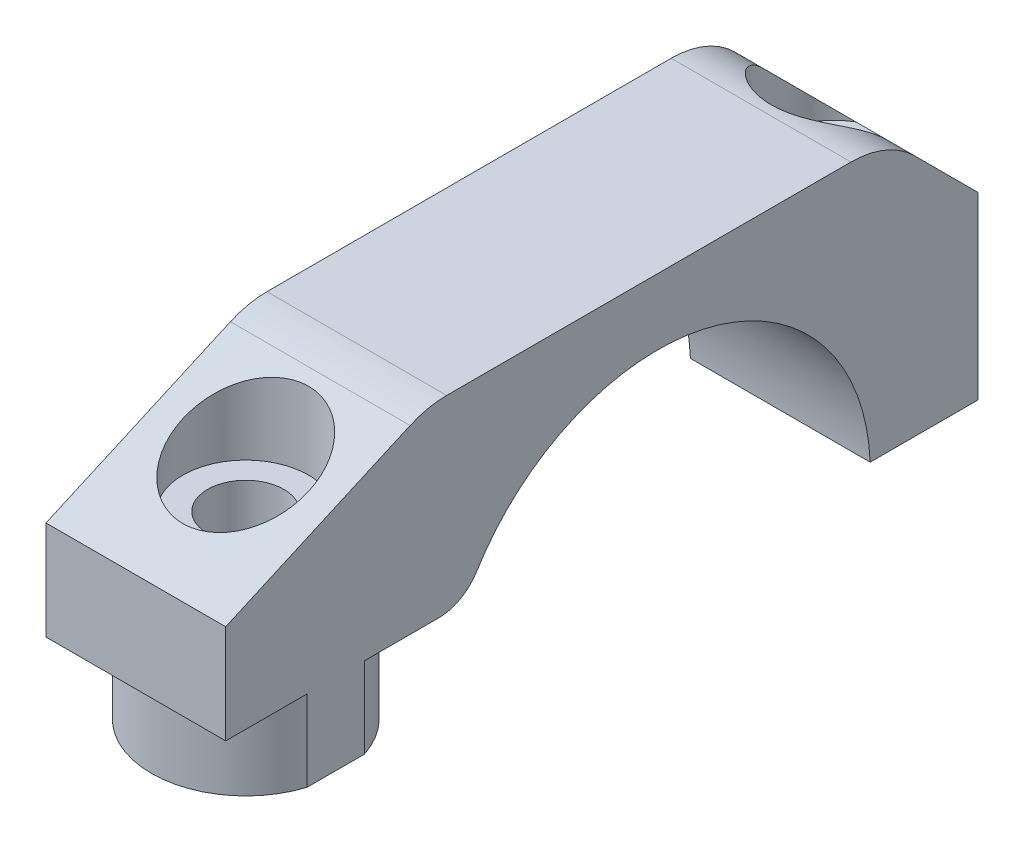
SolidWorks part; units mm, degrees
material "2014 Alloy"
ref_plane "Front Plane" through (0, 0, 0) normal (0, 0, 1) x (1, 0, 0)
ref_plane "Top Plane" through (0, 0, 0) normal (0, 1, 0) x (1, 0, 0)
ref_plane "Right Plane" through (0, 0, 0) normal (1, 0, 0) x (0, 0, -1)
sketch "Sketch1" plane through (0, 0, 0) normal (1, 0, 0) x (0, 0, -1)
  line L0 (-35.6288, 0) -> (35.6288, 0)
  line L1 (35.6288, 0) -> (35.6288, -30)
  line L2 (35.6288, -30) -> (23.6288, -30)
  line L3 (0, 0) -> (0, -31) construction
  line L4 (-24.6288, -30) -> (-48.0833, -30)
  line L5 (-35.6288, 0) -> (-35.6288, -30) construction
  line L6 (-24.6288, -30) -> (-24.6288, -21)
  line L7 (-48.0833, -30) -> (-48.0833, 0)
  line L8 (-48.0833, 0) -> (-35.6288, 0)
  line L9 (-24.6288, -21) -> (-21.4318, -21)
  arc A0 (23.6288, -30) -> (-21.4318, -21) centre (0, -31) ccw
  point P6 (-23.6288, -30)
  point P9 (-35.8561, -30)
  dimension "D1" = 23.65
  dimension "D2" = 12
  dimension "D3" = 30
  dimension "D4" = 35.87
  dimension "D5" = 1
  dimension "D6" = 9
  dimension "D7" = 11
  dimension "D8" = 83.7121
extrude "Boss-Extrude1" add sketch "Sketch1" along normal blind 20
chamfer "Chamfer1" distance 10 angle 45 1 edges at (10, 0, -35.6288)
chamfer "Chamfer2" distance 10 angle 66 1 edges at (10, 0, 48.0833)
fillet "Fillet2" radius 10 2 edges at (10, 0, -25.6288) (10, 0, 25.6229)
fillet "Fillet3" radius 5 1 edges at (10, -21, 21.4318)
hole_wizard "Ø8.5 (8.5) Diameter Hole1" positions "Sketch5" profile "Sketch4" hole size "Ø8.5" standard "ISO" end condition through all
sketch "Sketch5" plane through (0, -30, 0) normal (0, -1, 0) x (-1, 0, 0)
  line L0 (-10, -48.0833) -> (-10, -23.6288) construction
  line L4 (-10, 23.6288) -> (-10, 35.6288) construction
  line L5 (-20, 23.6288) -> (0, 23.6288) construction
  line L6 (-20, 35.6288) -> (0, 35.6288) construction
  line L8 (-20, -48.0833) -> (0, -48.0833) construction
  point P0 (-10, -35.8561)
  point P2 (-10, 29.6288)
sketch "Sketch4" plane through (10, -30, 35.8561) normal (1, 0, 0) x (0, 0, -1)
  line L0 (0, 0) -> (0, 30)
  line L1 (0, 30) -> (4.25, 30)
  line L2 (4.25, 30) -> (4.25, 0)
  line L5 (4.25, 0) -> (0, 0)
  line L11 (0, -6.35) -> (0, 107.95) construction
  dimension "Thru Hole Dia." = 8.5
  dimension "Thru Hole Depth" = 30
sketch "Sketch6" plane through (0, 0, 0) normal (0, 1, 0) x (1, 0, 0)
  circle A0 centre (10, -35.8561) radius 7
  circle A1 centre (10, 29.6288) radius 7
  circle A4 centre (10, -35.8561) radius 4.25 construction
  arc A5 (5.8872, 28.5578) -> (14.1128, 28.5578) centre (10, 29.6288) ccw construction
  dimension "D1" = 14
extrude "Cut-Extrude1" cut sketch "Sketch6" against normal blind 10
sketch "Sketch7" plane through (0, -30, 0) normal (0, -1, 0) x (1, 0, 0)
  circle A0 centre (10, 35.8561) radius 10.5
  circle A1 centre (10, 35.8561) radius 22.104
  dimension "D1" = 21
extrude "Cut-Extrude2" cut sketch "Sketch7" against normal offset from surface (9 mm away) 21 up to face at (10, 0, 1.0053)
sketch "Sketch8" [suppressed] plane through (20, 0, 0) normal (1, 0, 0) x (0, 0, -1)
  line L9 (-24.5288, -21) -> (-24.292, -21)
  line L10 (23.5288, -30) -> (35.5288, -30)
  line L11 (35.5288, -30) -> (35.5288, -10)
  line L12 (35.5288, -10) -> (28.4577, -2.9289)
  line L13 (21.3866, 0) -> (-23.5974, 0)
  line L14 (-27.6648, -0.8645) -> (-48.1834, -10)
  line L15 (-48.1834, -10) -> (-48.1834, -30)
  line L16 (-48.1834, -30) -> (-24.5288, -30)
  line L17 (-24.5288, -30) -> (-24.5288, -21)
  line L18 (-24.5288, -21) -> (-24.292, -21)
  line L19 (23.5288, -30) -> (35.5288, -30)
  line L20 (35.5288, -30) -> (35.5288, -10)
  line L21 (35.5288, -10) -> (28.4577, -2.9289)
  line L22 (21.3866, 0) -> (-23.5974, 0)
  line L23 (-27.6648, -0.8645) -> (-48.1834, -10)
  line L24 (-48.1834, -10) -> (-48.1834, -30)
  line L25 (-48.1834, -30) -> (-24.5288, -30)
  line L26 (-24.5288, -30) -> (-24.5288, -21)
  arc A4 (-24.292, -21) -> (-20.0377, -18.627) centre (-24.292, -16) ccw
  arc A5 (23.5288, -30) -> (-20.0377, -18.627) centre (0, -31) ccw
  arc A6 (28.4577, -2.9289) -> (21.3866, 0) centre (21.3866, -10) ccw
  arc A7 (-23.5974, 0) -> (-27.6648, -0.8645) centre (-23.5974, -10) ccw
  arc A8 (-24.292, -21) -> (-20.0377, -18.627) centre (-24.292, -16) ccw
  arc A9 (23.5288, -30) -> (-20.0377, -18.627) centre (0, -31) ccw
  arc A10 (28.4577, -2.9289) -> (21.3866, 0) centre (21.3866, -10) ccw
  arc A11 (-23.5974, 0) -> (-27.6648, -0.8645) centre (-23.5974, -10) ccw
  dimension "D1" = 0
extrude "Boss-Extrude2" [suppressed] add sketch "Sketch8" along normal blind 5
sketch "Sketch9" [suppressed] plane through (25, 0, 0) normal (1, 0, 0) x (0, 0, -1)
  line L0 (-23.5288, -31) -> (-23.5288, -21.9513)
  line L1 (-23.5288, -21.9513) -> (-23.5288, -21.9513)
  line L2 (22.55, -31) -> (36.5288, -31)
  line L3 (36.5288, -31) -> (36.5288, -9.5858)
  line L4 (36.5288, -9.5858) -> (29.1648, -2.2218)
  line L5 (21.3866, 1) -> (-23.5974, 1)
  line L6 (-28.0715, 0.049) -> (-49.1834, -9.3506)
  line L7 (-49.1834, -9.3506) -> (-49.1834, -31)
  line L8 (-49.1834, -31) -> (-23.5288, -31)
  line L9 (-24.5288, -30) -> (-24.5288, -21)
  line L10 (-24.5288, -21) -> (-24.292, -21)
  line L11 (23.5288, -30) -> (35.5288, -30)
  line L12 (35.5288, -30) -> (35.5288, -10)
  line L13 (35.5288, -10) -> (28.4577, -2.9289)
  line L14 (21.3866, 0) -> (-23.5974, 0)
  line L15 (-27.6648, -0.8645) -> (-48.1834, -10)
  line L16 (-48.1834, -10) -> (-48.1834, -30)
  line L17 (-48.1834, -30) -> (-24.5288, -30)
  line L18 (-24.5288, -30) -> (-24.5288, -21)
  line L19 (-24.5288, -21) -> (-24.292, -21)
  line L20 (23.5288, -30) -> (35.5288, -30)
  line L21 (35.5288, -30) -> (35.5288, -10)
  line L22 (35.5288, -10) -> (28.4577, -2.9289)
  line L23 (21.3866, 0) -> (-23.5974, 0)
  line L24 (-27.6648, -0.8645) -> (-48.1834, -10)
  line L25 (-48.1834, -10) -> (-48.1834, -30)
  line L26 (-48.1834, -30) -> (-24.5288, -30)
  arc A0 (-23.5288, -21.9513) -> (-19.1869, -19.1524) centre (-24.292, -16) ccw
  arc A1 (22.55, -31) -> (-19.1869, -19.1524) centre (0, -31) ccw
  arc A2 (29.1648, -2.2218) -> (21.3866, 1) centre (21.3866, -10) ccw
  arc A3 (-23.5974, 1) -> (-28.0715, 0.049) centre (-23.5974, -10) ccw
  arc A4 (-24.292, -21) -> (-20.0377, -18.627) centre (-24.292, -16) ccw
  arc A5 (23.5288, -30) -> (-20.0377, -18.627) centre (0, -31) ccw
  arc A6 (28.4577, -2.9289) -> (21.3866, 0) centre (21.3866, -10) ccw
  arc A7 (-23.5974, 0) -> (-27.6648, -0.8645) centre (-23.5974, -10) ccw
  arc A8 (-24.292, -21) -> (-20.0377, -18.627) centre (-24.292, -16) ccw
  arc A9 (23.5288, -30) -> (-20.0377, -18.627) centre (0, -31) ccw
  arc A10 (28.4577, -2.9289) -> (21.3866, 0) centre (21.3866, -10) ccw
  arc A11 (-23.5974, 0) -> (-27.6648, -0.8645) centre (-23.5974, -10) ccw
  dimension "D1" = 0
  dimension "D2" = 1
extrude "Boss-Extrude3" [suppressed] add sketch "Sketch9" against normal blind 25
